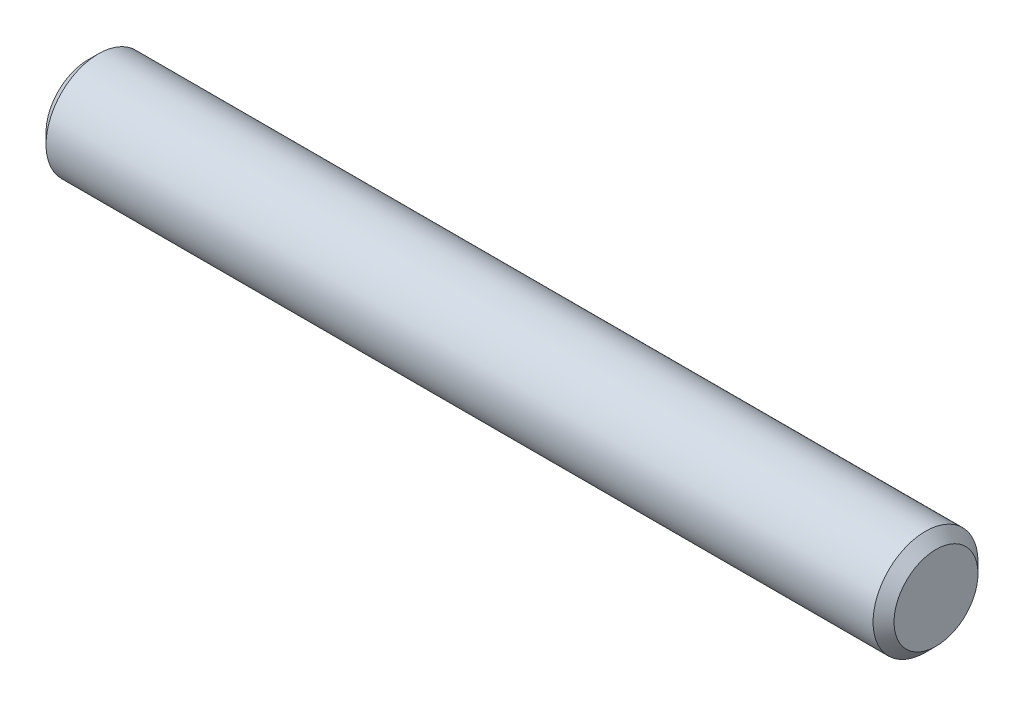
SolidWorks part; units mm, degrees
ref_plane "Front Plane" through (0, 0, 0) normal (0, 0, 1) x (1, 0, 0)
ref_plane "Top Plane" through (0, 0, 0) normal (0, 1, 0) x (1, 0, 0)
ref_plane "Right Plane" through (0, 0, 0) normal (1, 0, 0) x (0, 0, -1)
sketch "Sketch1" plane through (0, 0, 0) normal (1, 0, 0) x (0, 0, -1)
  circle A0 centre (0, 0) radius 5
  dimension "D1" = 10
extrude "Boss-Extrude1" add sketch "Sketch1" along normal blind 80.8
chamfer "Chamfer1" distance 1 angle 45 2 edges at (80.8, 0, -5) (0, 0, -5)
